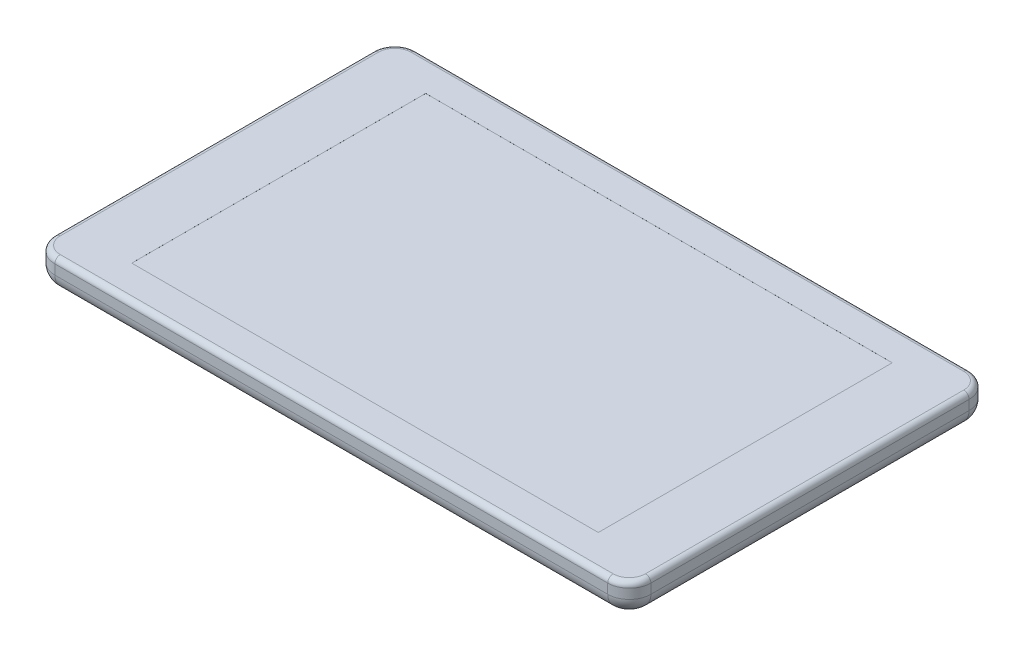
SolidWorks part; units mm, degrees
ref_plane "Front Plane" through (0, 0, 0) normal (0, 0, 1) x (1, 0, 0)
ref_plane "Top Plane" through (0, 0, 0) normal (0, 1, 0) x (1, 0, 0)
ref_plane "Right Plane" through (0, 0, 0) normal (1, 0, 0) x (0, 0, -1)
sketch "Sketch1" plane through (0, 0, 0) normal (0, 1, 0) x (1, 0, 0)
  line L1 (110.5, -67) -> (-110.5, -67)
  line L2 (110.5, -67) -> (110.5, 67)
  line L3 (110.5, 67) -> (-110.5, 67)
  line L4 (-110.5, -67) -> (-110.5, 67)
  line L5 (110.5, -67) -> (-110.5, 67) construction
  line L6 (110.5, 67) -> (-110.5, -67) construction
  point P0 (0, 0)
  dimension "D1" = 221
  dimension "D2" = 134
extrude "Boss-Extrude1" add sketch "Sketch1" along normal blind 11.6
fillet "Fillet1" radius 8 4 edges at (-110.5, 5.8, -67) (110.5, 5.8, -67) (110.5, 5.8, 67) (-110.5, 5.8, 67)
fillet "Fillet2" radius 2 8 edges at (108.1569, 11.6, -64.6569) (110.5, 11.6, 0) (108.1569, 11.6, 64.6569) (0, 11.6, 67) (-108.1569, 11.6, 64.6569) (-110.5, 11.6, 0) (-108.1569, 11.6, -64.6569) (0, 11.6, -67)
fillet "Fillet3" radius 6 8 edges at (-108.1569, 0, 64.6569) (0, 0, 67) (108.1569, 0, 64.6569) (110.5, 0, 0) (108.1569, 0, -64.6569) (0, 0, -67) (-108.1569, 0, -64.6569) (-110.5, 0, 0)
sketch "Sketch2" plane through (0, 11.6, 0) normal (0, 1, 0) x (1, 0, 0)
  line L1 (86.5, -54.5) -> (-86.5, -54.5)
  line L2 (86.5, -54.5) -> (86.5, 54.5)
  line L3 (86.5, 54.5) -> (-86.5, 54.5)
  line L4 (-86.5, -54.5) -> (-86.5, 54.5)
  line L5 (86.5, -54.5) -> (-86.5, 54.5) construction
  line L6 (86.5, 54.5) -> (-86.5, -54.5) construction
  point P0 (0, 0)
  dimension "D1" = 109
  dimension "D2" = 173
extrude "Cut-Extrude1" cut sketch "Sketch2" against normal blind 0.01
